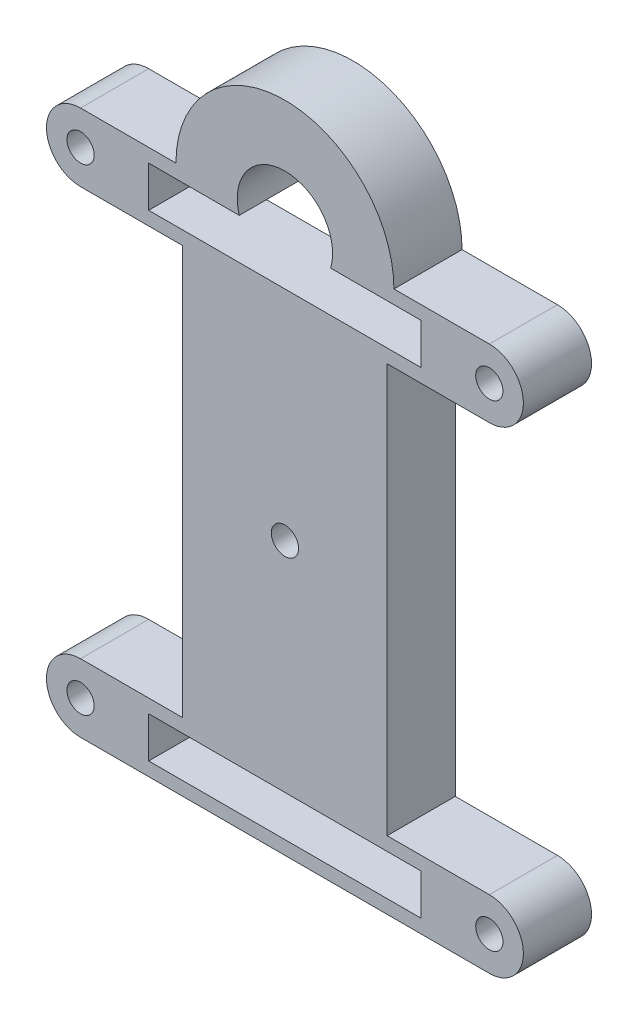
SolidWorks part; units mm, degrees
ref_plane "Front Plane" through (0, 0, 0) normal (0, 0, 1) x (1, 0, 0)
ref_plane "Top Plane" through (0, 0, 0) normal (0, 1, 0) x (1, 0, 0)
ref_plane "Right Plane" through (0, 0, 0) normal (1, 0, 0) x (0, 0, -1)
sketch "Sketch1" plane through (0, 0, 0) normal (0, 0, 1) x (1, 0, 0)
  line L0 (-15, 17.5) -> (15, 17.5) construction
  line L1 (7.5, 15) -> (15, 15)
  line L2 (-7.5, 15) -> (-7.5, -15)
  line L3 (-7.5, -15) -> (7.5, -15) construction
  line L4 (7.5, 15) -> (7.5, -15)
  line L5 (-7.5, 15) -> (7.5, -15) construction
  line L6 (-7.5, -15) -> (7.5, 15) construction
  line L7 (-15, 20) -> (-8, 20)
  line L8 (-15, 15) -> (-7.5, 15)
  line L9 (-32.3549, 0) -> (39.4021, 0) construction
  line L10 (-15, -17.5) -> (15, -17.5) construction
  line L11 (-15, -15) -> (-7.5, -15)
  line L12 (-15, -20) -> (15, -20)
  line L13 (7.5, -15) -> (15, -15)
  line L14 (15, 20) -> (8, 20)
  arc A0 (-15, 20) -> (-15, 15) centre (-15, 17.5) ccw
  arc A1 (15, 15) -> (15, 20) centre (15, 17.5) ccw
  circle A2 centre (-15, 17.5) radius 1
  circle A3 centre (15, 17.5) radius 1
  circle A4 centre (15, -17.5) radius 1
  circle A5 centre (-15, -17.5) radius 1
  arc A6 (15, -15) -> (15, -20) centre (15, -17.5) cw
  arc A7 (-15, -20) -> (-15, -15) centre (-15, -17.5) cw
  circle A8 centre (0, 20) radius 3.5
  arc A9 (8, 20) -> (-8, 20) centre (0, 20) ccw
  point P0 (0, 0)
  point P8 (0, 20)
  point P25 (0, -20)
  dimension "D3" = 2.5
  dimension "D6" = 2.5
  dimension "D7" = 2
  dimension "D8" = 2
  dimension "D9" = 7
  dimension "D10" = 8
  dimension "D1" = 30
  dimension "D2" = 15
  dimension "D4" = 30
  dimension "D5" = 7.5
extrude "Boss-Extrude2" add sketch "Sketch1" along normal mid plane 5
sketch "Sketch2" plane through (0, 0, 2.5) normal (0, 0, 1) x (1, 0, 0)
  line L0 (0, 25.1089) -> (0, -5.5376) construction
  line L1 (-15, -20) -> (15, -20) construction
  line L2 (-7.5, -15) -> (-15, -15) construction
  line L3 (-8, 20) -> (-15, 20) construction
  line L4 (-10, 19) -> (10, 19)
  line L6 (-23.3833, 0) -> (29.3707, 0) construction
  line L7 (10, -19) -> (10, -16)
  line L8 (-10, -16) -> (10, -16)
  line L9 (-10, -19) -> (-10, -16)
  line L10 (-10, -19) -> (10, -19)
  line L11 (-10, 19) -> (-10, 16)
  line L12 (-10, 16) -> (10, 16)
  line L13 (10, 19) -> (10, 16)
  line L14 (-10, 19) -> (10, 16) construction
  line L15 (-10, 16) -> (10, 19) construction
  circle A0 centre (0, 0) radius 1
  point P9 (0, 17.5)
  dimension "D1" = 2
  dimension "D2" = 20
  dimension "D3" = 3
  dimension "D4" = 1
  dimension "D5" = 1
  dimension "D6" = 3
  dimension "D7" = 20
  dimension "D8" = 1
extrude "Cut-Extrude1" cut sketch "Sketch2" against normal through all
